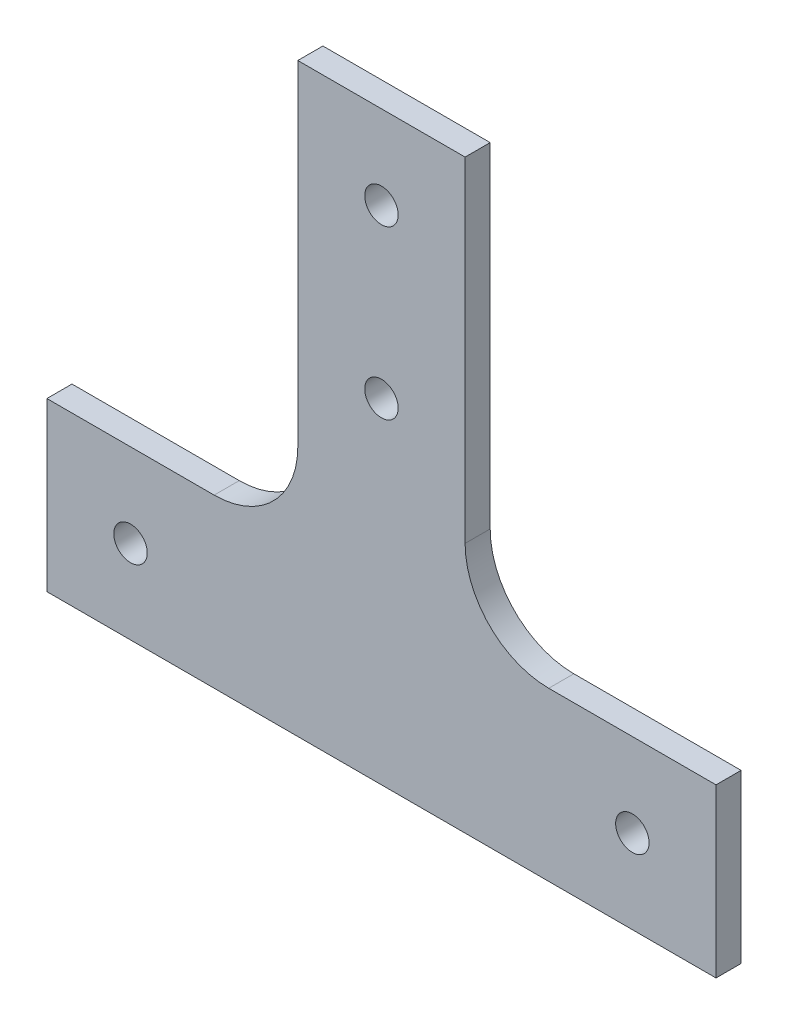
SolidWorks part; units mm, degrees
ref_plane "前视基准面" through (0, 0, 0) normal (0, 0, 1) x (1, 0, 0)
ref_plane "上视基准面" through (0, 0, 0) normal (0, 1, 0) x (1, 0, 0)
ref_plane "右视基准面" through (0, 0, 0) normal (1, 0, 0) x (0, 0, -1)
sketch "草图1" plane through (0, 0, 0) normal (0, 0, 1) x (1, 0, 0)
  line L0 (0, -1000) -> (0, 49000) construction
  line L1 (-40, 10) -> (40, 10)
  line L2 (-40, 10) -> (-40, -10)
  line L3 (-40, -10) -> (40, -10)
  line L4 (40, 10) -> (40, -10)
  line L5 (-40, 10) -> (40, -10) construction
  line L6 (-40, -10) -> (40, 10) construction
  line L7 (-10, 10) -> (10, 10)
  line L8 (-10, 10) -> (-10, 60)
  line L9 (-10, 60) -> (10, 60)
  line L10 (10, 10) -> (10, 60)
  line L11 (-1000, 0) -> (49000, 0) construction
  circle A0 centre (-30, 0) radius 2
  circle A1 centre (30, 0) radius 2
  circle A2 centre (0, 30) radius 2
  circle A3 centre (0, 50) radius 2
  point P0 (0, 0)
  point P10 (0, 60)
  dimension "D5" = 4
  dimension "D6" = 4
  dimension "D7" = 30
  dimension "D8" = 30
  dimension "D9" = 4
  dimension "D10" = 4
  dimension "D11" = 20
  dimension "D12" = 20
  dimension "D1" = 20
  dimension "D2" = 80
  dimension "D3" = 50
  dimension "D4" = 20
extrude "凸台-拉伸1" add sketch "草图1" along normal blind 3 contours L1 L10 L9 L8 A3 A2 | L4 L1 L2 L3 A1 A0
fillet "圆角1" radius 10 2 edges at (-10, 10, 1.5) (10, 10, 1.5)
